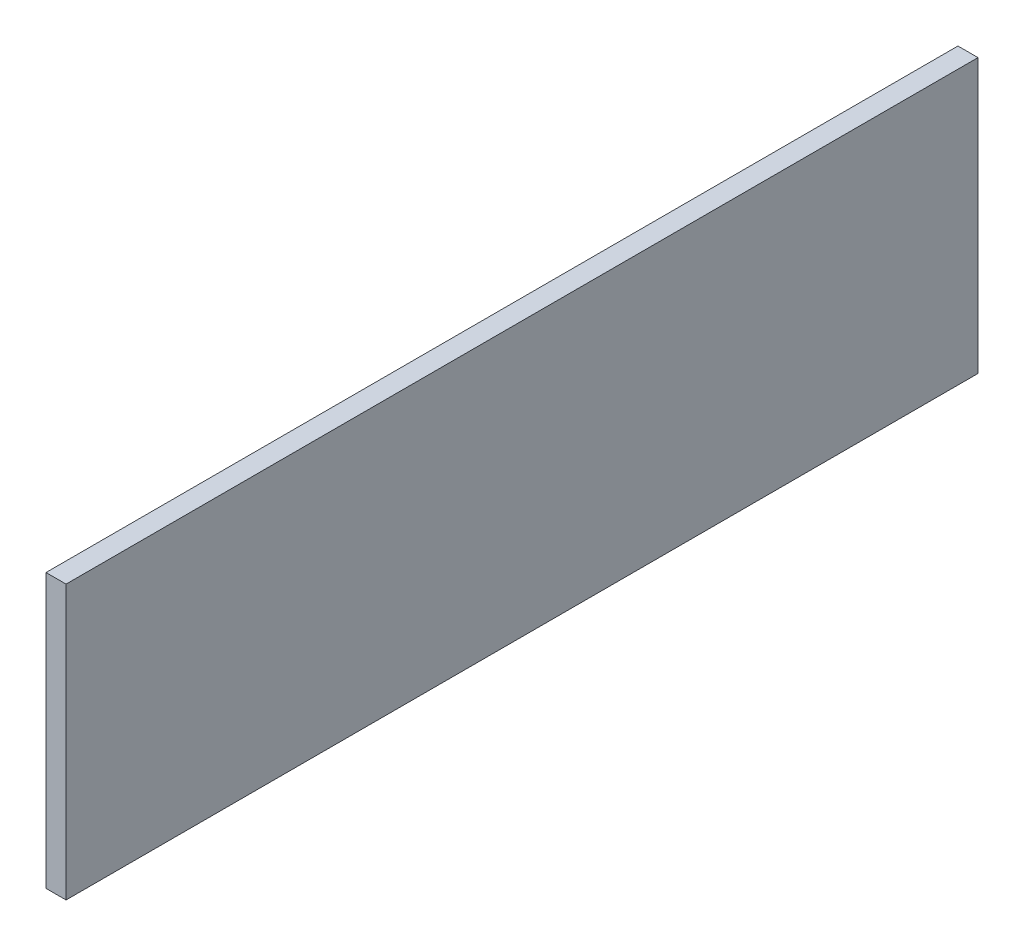
SolidWorks part; units mm, degrees
ref_plane "Front Plane" through (0, 0, 0) normal (0, 0, 1) x (1, 0, 0)
ref_plane "Top Plane" through (0, 0, 0) normal (0, 1, 0) x (1, 0, 0)
ref_plane "Right Plane" through (0, 0, 0) normal (1, 0, 0) x (0, 0, -1)
sketch "Sketch1" plane through (0, 0, 0) normal (1, 0, 0) x (0, 0, -1)
  line L1 (-127, -38.1) -> (127, -38.1)
  line L2 (-127, -38.1) -> (-127, 38.1)
  line L3 (-127, 38.1) -> (127, 38.1)
  line L4 (127, -38.1) -> (127, 38.1)
  line L5 (-127, -38.1) -> (127, 38.1) construction
  line L6 (-127, 38.1) -> (127, -38.1) construction
  point P0 (0, 0)
  dimension "D1" = 254
  dimension "D2" = 76.2
extrude "Boss-Extrude1" add sketch "Sketch1" along normal blind 5.588
